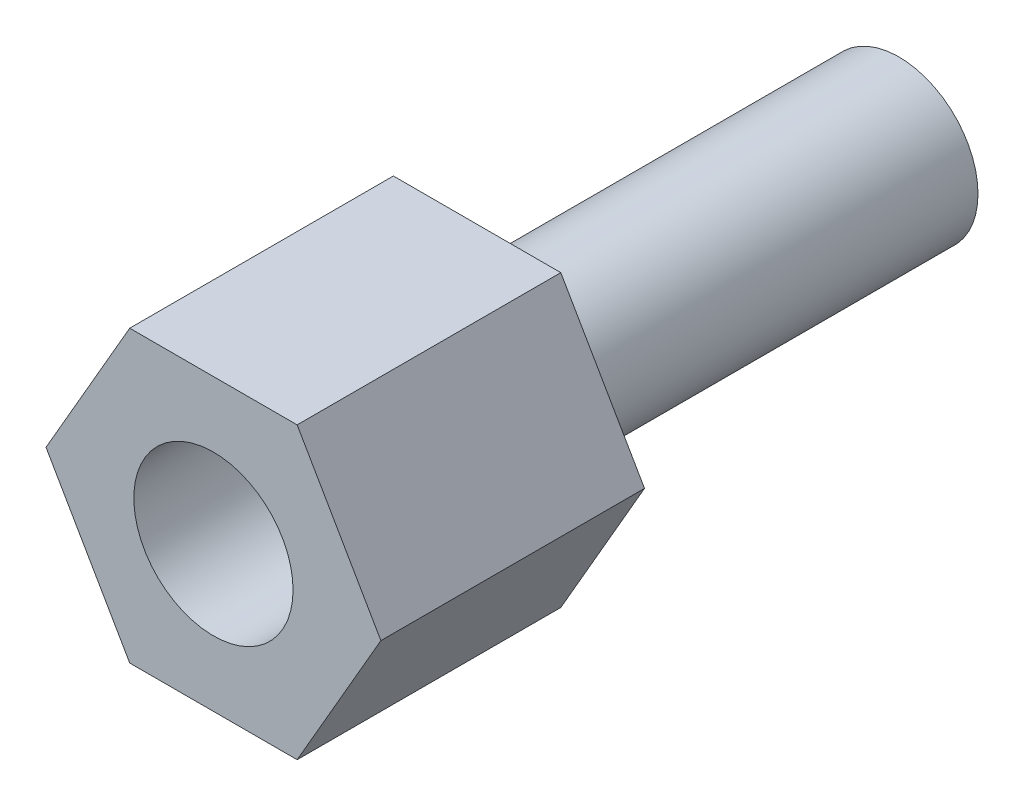
SolidWorks part; units mm, degrees
ref_plane "前视基准面" through (0, 0, 0) normal (0, 0, 1) x (1, 0, 0)
ref_plane "上视基准面" through (0, 0, 0) normal (0, 1, 0) x (1, 0, 0)
ref_plane "右视基准面" through (0, 0, 0) normal (1, 0, 0) x (0, 0, -1)
other "Configuration Table"
sketch "Female_hex_standoff_Sketch" plane through (0, 0, 0) normal (0, 0, 1) x (1, 0, 0)
  line L0 (3.1754, 0) -> (1.5877, 2.75)
  line L1 (1.5877, 2.75) -> (-1.5877, 2.75)
  line L2 (-1.5877, 2.75) -> (-3.1754, 0)
  line L3 (-3.1754, 0) -> (-1.5877, -2.75)
  line L4 (-1.5877, -2.75) -> (1.5877, -2.75)
  line L5 (1.5877, -2.75) -> (3.1754, 0)
  circle A0 centre (0, 0) radius 1.51
extrude "Female_hex_standoff" add sketch "Female_hex_standoff_Sketch" along normal blind 5 separate body
sketch "Stud_root_Sketch" plane through (0, 0, 0) normal (0, 0, 1) x (1, 0, 0)
  circle A0 centre (0, 0) radius 1.85
extrude "Stud_root" add sketch "Stud_root_Sketch" along normal blind 0.45
sketch "Male_thread_envelope_Sketch" plane through (0, 0, 0) normal (0, 0, 1) x (1, 0, 0)
  circle A0 centre (0, 0) radius 1.5
extrude "Male_thread_envelope" add sketch "Male_thread_envelope_Sketch" along normal blind 8 from offset 8
